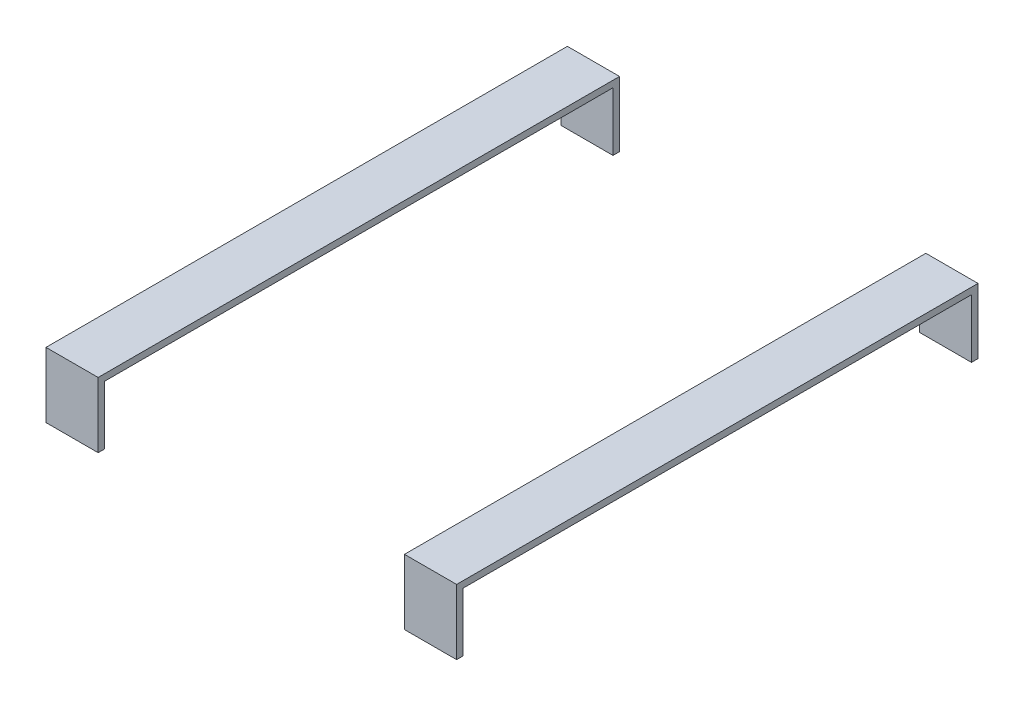
SolidWorks part; units mm, degrees
ref_plane "Alzado" through (0, 0, 0) normal (0, 0, 1) x (1, 0, 0)
ref_plane "Planta" through (0, 0, 0) normal (0, 1, 0) x (1, 0, 0)
ref_plane "Vista lateral" through (0, 0, 0) normal (1, 0, 0) x (0, 0, -1)
sketch "Croquis1" plane through (0, 0, 0) normal (0, 1, 0) x (1, 0, 0)
  line L0 (0, 0) -> (470, 0) construction
  line L1 (0, 0) -> (-80, 0)
  line L2 (0, 0) -> (0, -10)
  line L3 (0, -10) -> (-80, -10)
  line L4 (-80, 0) -> (-80, -10)
  line L5 (-80, -10) -> (-80, -400) construction
  line L6 (470, 0) -> (550, 0)
  line L7 (470, 0) -> (470, -10)
  line L8 (470, -10) -> (550, -10)
  line L9 (550, 0) -> (550, -10)
  line L10 (-80, -400) -> (239.0685, -400) construction
  line L11 (0, -800) -> (470, -800) construction
  line L12 (550, -800) -> (550, -790)
  line L13 (470, -790) -> (550, -790)
  line L14 (470, -800) -> (470, -790)
  line L15 (470, -800) -> (550, -800)
  line L16 (-80, -800) -> (-80, -790)
  line L17 (0, -790) -> (-80, -790)
  line L18 (0, -800) -> (0, -790)
  line L19 (0, -800) -> (-80, -800)
  dimension "D1" = 10
  dimension "D2" = 80
  dimension "D3" = 470
  dimension "D4" = 80
  dimension "D5" = 10
  dimension "D6" = 390
extrude "Saliente-Extruir1" add sketch "Croquis1" along normal blind 100
sketch "Croquis2" plane through (0, 0, 10) normal (0, 0, 1) x (1, 0, 0)
  line L0 (0, 100) -> (0, 0) construction
  line L1 (-80, 100) -> (0, 100)
  line L2 (-80, 100) -> (-80, 90)
  line L3 (-80, 90) -> (0, 90)
  line L4 (0, 100) -> (0, 90)
  line L5 (550, 100) -> (550, 0) construction
  line L6 (470, 100) -> (550, 100)
  line L7 (470, 100) -> (470, 90)
  line L8 (470, 90) -> (550, 90)
  line L9 (550, 100) -> (550, 90)
  dimension "D1" = 10
  dimension "D2" = 10
extrude "Saliente-Extruir2" add sketch "Croquis2" along normal up to surface (780 mm away) up to face at (510, 50, 790)
